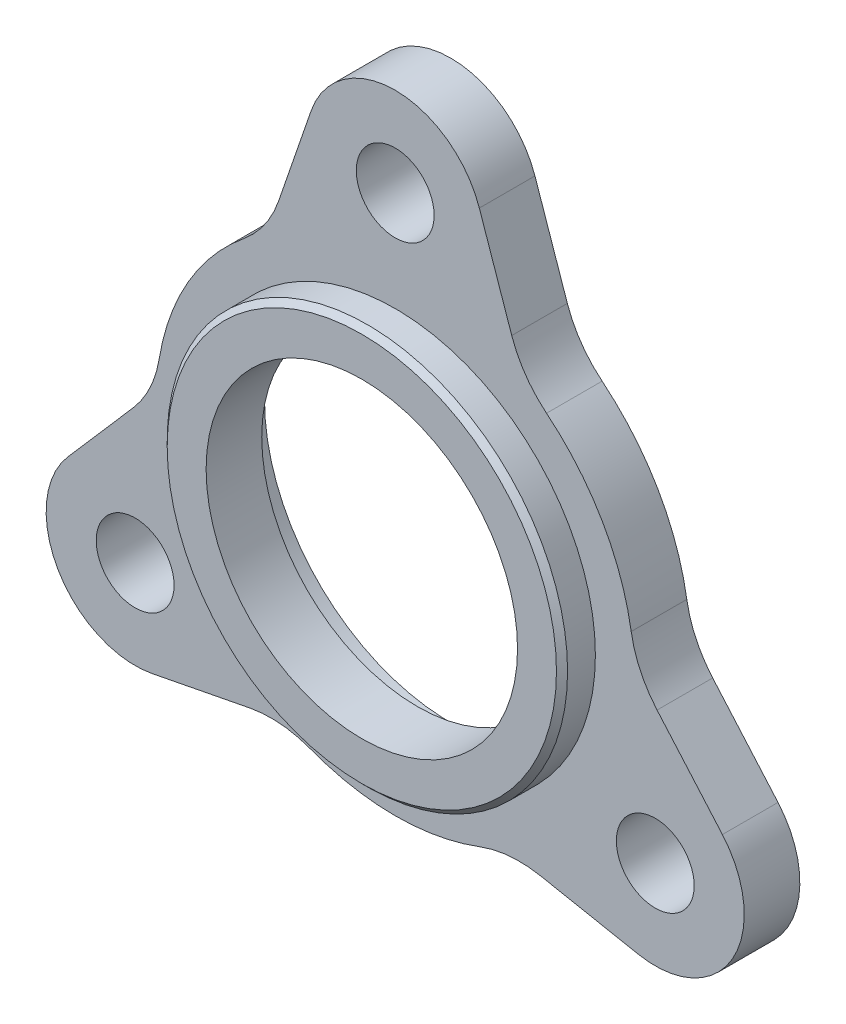
SolidWorks part; units mm, degrees
material "AISI 1010 钢，热轧条材"
ref_plane "前视基准面" through (0, 0, 0) normal (0, 0, 1) x (1, 0, 0)
ref_plane "上视基准面" through (0, 0, 0) normal (0, 1, 0) x (1, 0, 0)
ref_plane "右视基准面" through (0, 0, 0) normal (1, 0, 0) x (0, 0, -1)
sketch "草图1" plane through (0, 0, 0) normal (0, 0, 1) x (1, 0, 0)
  line L0 (-11.5, 18.1659) -> (-7.5647, 29.6029)
  line L1 (0, 0) -> (0, 39.4904) construction
  line L2 (11.5, 18.1659) -> (7.5647, 29.6029)
  line L3 (21.4821, 0.8763) -> (29.4192, -8.2502)
  line L4 (9.9821, -19.0422) -> (21.8545, -21.3527)
  line L5 (-9.9821, -19.0422) -> (-21.8545, -21.3527)
  line L6 (-21.4821, 0.8763) -> (-29.4192, -8.2502)
  arc A0 (-11.5, 18.1659) -> (-21.4821, 0.8763) centre (0, 0) ccw
  circle A1 centre (0, 0) radius 27 construction
  arc A2 (7.5647, 29.6029) -> (-7.5647, 29.6029) centre (0, 27) ccw
  arc A3 (21.8545, -21.3527) -> (29.4192, -8.2502) centre (23.3827, -13.5) ccw
  arc A4 (-29.4192, -8.2502) -> (-21.8545, -21.3527) centre (-23.3827, -13.5) ccw
  arc A5 (21.4821, 0.8763) -> (11.5, 18.1659) centre (0, 0) ccw
  arc A6 (-9.9821, -19.0422) -> (9.9821, -19.0422) centre (0, 0) ccw
  circle A7 centre (0, 27) radius 3.5
  circle A8 centre (23.3827, -13.5) radius 3.5
  circle A9 centre (-23.3827, -13.5) radius 3.5
  point P23 (0, 0)
  point P28 (0, 0)
  dimension "D1" = 43
  dimension "D2" = 54
  dimension "D3" = 16
  dimension "D4" = 3
  dimension "D6" = 7
  dimension "D7" = 3
  dimension "D5" = 23
extrude "凸台-拉伸1" add sketch "草图1" along normal blind 5
fillet "圆角1" radius 10 6 edges at (-9.9821, -19.0422, 2.5) (9.9821, -19.0422, 2.5) (21.4821, 0.8763, 2.5) (11.5, 18.1659, 2.5) (-21.4821, 0.8763, 2.5) (-11.5, 18.1659, 2.5)
sketch "草图2" plane through (0, 0, 5) normal (0, 0, 1) x (1, 0, 0)
  circle A0 centre (0, 0) radius 18
  dimension "D1" = 36
extrude "凸台-拉伸2" add sketch "草图2" along normal blind 3
sketch "草图3" plane through (0, 0, 8) normal (0, 0, 1) x (1, 0, 0)
  circle A0 centre (0, 0) radius 14
  dimension "D1" = 28
extrude "切除-拉伸1" cut sketch "草图3" against normal blind 32
sketch "草图4" plane through (0, 0, 0) normal (0, 0, -1) x (-1, 0, 0)
  circle A0 centre (0, 0) radius 16.75
  dimension "D1" = 33.5
extrude "切除-拉伸2" cut sketch "草图4" against normal blind 3
chamfer "倒角1" distance 0.5 angle 45 1 edges at (18, 0, 8)
